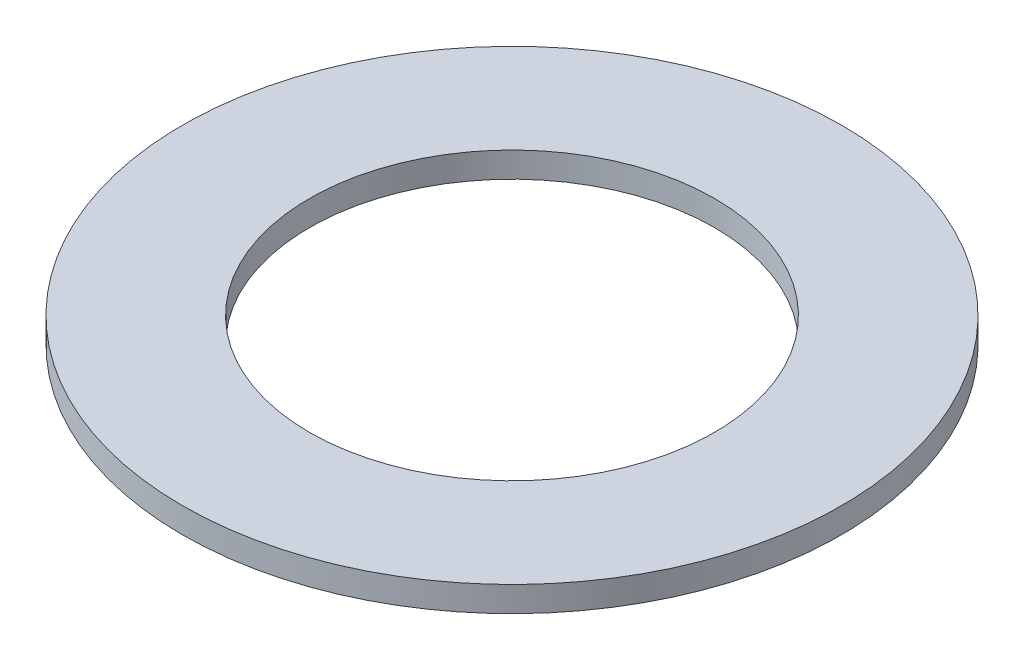
SolidWorks part; units mm, degrees
ref_plane "Front Plane" through (0, 0, 0) normal (0, 0, 1) x (1, 0, 0)
ref_plane "Top Plane" through (0, 0, 0) normal (0, 1, 0) x (1, 0, 0)
ref_plane "Right Plane" through (0, 0, 0) normal (1, 0, 0) x (0, 0, -1)
sketch "Sketch1" plane through (0, 0, 0) normal (0, 1, 0) x (1, 0, 0)
  circle A0 centre (0, 0) radius 7.825
  circle A1 centre (0, 0) radius 4.81
  dimension "D1" = 15.65
  dimension "D2" = 9.62
extrude "Boss-Extrude1" add sketch "Sketch1" along normal blind 0.6
